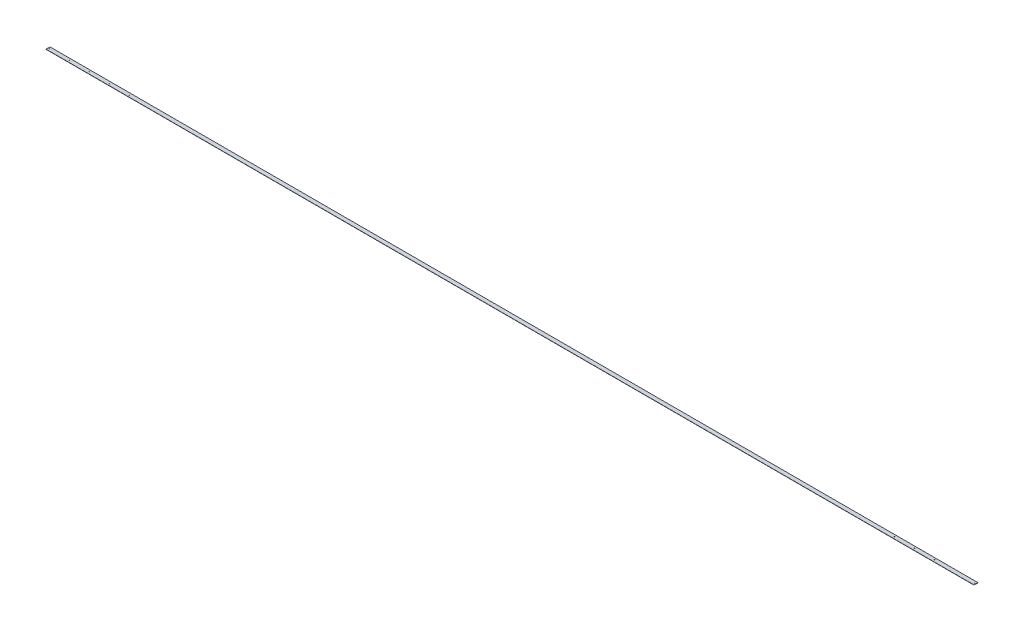
SolidWorks part; units mm, degrees
material "5052-H32"
ref_plane "Front Plane" through (0, 0, 0) normal (0, 0, 1) x (1, 0, 0)
ref_plane "Top Plane" through (0, 0, 0) normal (0, 1, 0) x (1, 0, 0)
ref_plane "Right Plane" through (0, 0, 0) normal (1, 0, 0) x (0, 0, -1)
sketch "Sketch1" plane through (0, 0, 0) normal (0, 1, 0) x (1, 0, 0)
  line L1 (4925, -21) -> (-4925, -21)
  line L2 (4925, -21) -> (4925, 21)
  line L3 (4925, 21) -> (-4925, 21)
  line L4 (-4925, -21) -> (-4925, 21)
  line L5 (4925, -21) -> (-4925, 21) construction
  line L6 (4925, 21) -> (-4925, -21) construction
  point P0 (0, 0)
  dimension "D1" = 42
  dimension "D2" = 9850
extrude "Boss-Extrude1" add sketch "Sketch1" along normal blind 2
sketch "Sketch2" plane through (0, 2, 0) normal (0, 1, 0) x (1, 0, 0)
  line L0 (-4925, -21) -> (4925, -21) construction
  line L1 (-4925, 21) -> (-4925, -21) construction
  line L2 (4925, -21) -> (4925, 21) construction
  circle A0 centre (-4910, -1) radius 3.4
  circle A1 centre (-4697.5, -1) radius 3.4
  circle A2 centre (-4485, -1) radius 3.4
  circle A3 centre (-4272.5, -1) radius 3.4
  circle A4 centre (-4060, -1) radius 3.4
  circle A5 centre (4910, -1) radius 3.4
  circle A6 centre (4697.5, -1) radius 3.4
  circle A7 centre (4485, -1) radius 3.4
  circle A8 centre (4272.5, -1) radius 3.4
  circle A9 centre (4060, -1) radius 3.4
  dimension "D1" = 6.8
  dimension "D5" = 212.5
  dimension "D8" = 5
  dimension "D2" = 20
  dimension "D3" = 15
  dimension "D6" = 15
  dimension "D7" = 20
  dimension "D9" = 212.5
  dimension "D4" = 5
extrude "Cut-Extrude1" cut sketch "Sketch2" against normal blind 10
